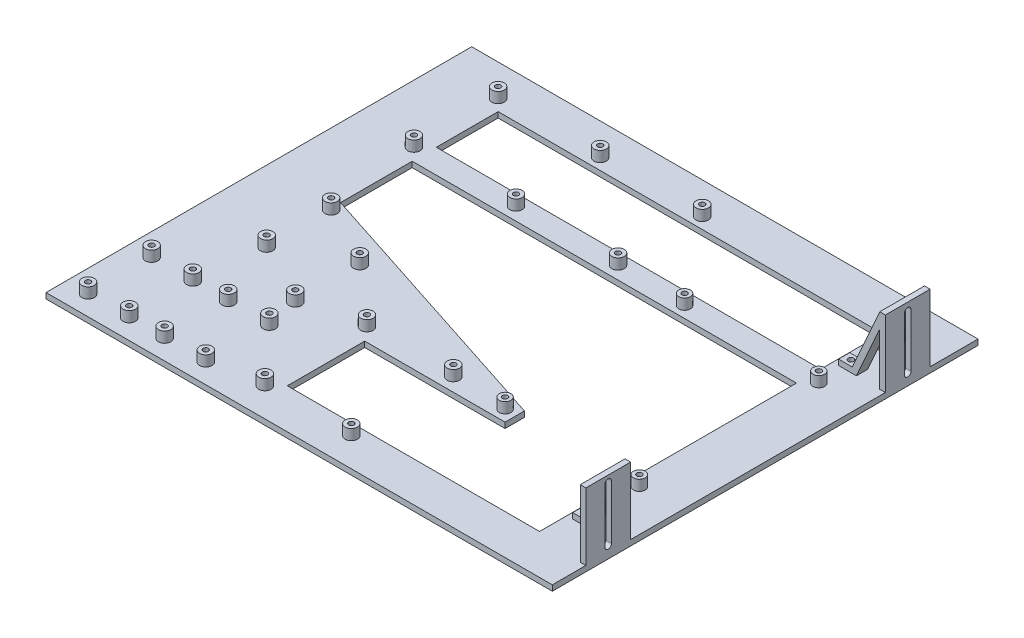
SolidWorks part; units mm, degrees
ref_plane "Front Plane" through (0, 0, 0) normal (0, 0, 1) x (1, 0, 0)
ref_plane "Top Plane" through (0, 0, 0) normal (0, 1, 0) x (1, 0, 0)
ref_plane "Right Plane" through (0, 0, 0) normal (1, 0, 0) x (0, 0, -1)
sketch "Sketch1" plane through (0, 0, 0) normal (0, 1, 0) x (1, 0, 0)
  line L1 (-143.637, -120.777) -> (143.637, -120.777)
  line L2 (-143.637, -120.777) -> (-143.637, 120.777)
  line L3 (-143.637, 120.777) -> (143.637, 120.777)
  line L4 (143.637, -120.777) -> (143.637, 120.777)
  line L5 (-143.637, -120.777) -> (143.637, 120.777) construction
  line L6 (-143.637, 120.777) -> (143.637, -120.777) construction
  point P0 (0, 0)
  dimension "D1" = 287.274
  dimension "D2" = 241.554
extrude "Boss-Extrude1" add sketch "Sketch1" along normal blind 3.175
sketch "Sketch2" plane through (0, 3.175, 0) normal (0, 1, 0) x (1, 0, 0)
  line L0 (-143.637, 93.599) -> (-143.637, 68.199)
  line L2 (-140.462, 93.599) -> (-143.637, 93.599)
  line L6 (-140.462, 68.199) -> (-140.462, 93.599)
  line L7 (-146.812, 68.199) -> (-140.462, 93.599) construction
  line L8 (-146.812, 93.599) -> (-140.462, 68.199) construction
  line L9 (-140.462, 68.199) -> (-143.637, 68.199)
  line L10 (0, 120.777) -> (0, 106.0603)
  line L11 (143.637, 120.777) -> (-143.637, 120.777) construction
  line L12 (146.812, 93.599) -> (140.462, 68.199) construction
  line L13 (146.812, 68.199) -> (140.462, 93.599) construction
  line L14 (140.462, 68.199) -> (143.637, 68.199)
  line L15 (140.462, 68.199) -> (140.462, 93.599)
  line L16 (140.462, 93.599) -> (143.637, 93.599)
  line L17 (143.637, 93.599) -> (143.637, 68.199)
  line M6 (143.637, -120.777) -> (143.637, 120.777)
  dimension "D2" = 25.4
  dimension "D3" = 6.35
extrude "Boss-Extrude3" add sketch "Sketch2" along normal blind 38.1 contours L16 L15 L14 M6
sketch "Sketch3" plane through (140.462, 0, 0) normal (-1, 0, 0) x (0, 0, 1)
  line L0 (-80.899, 36.6569) -> (-80.899, 6.3832) construction
  line L1 (-78.994, 36.6569) -> (-78.994, 6.3832)
  line L2 (-82.804, 36.6569) -> (-82.804, 6.3832)
  line L3 (-93.599, 41.275) -> (-93.599, 3.175) construction
  line L4 (-68.199, 41.275) -> (-68.199, 3.175) construction
  arc A0 (-78.994, 36.6569) -> (-82.804, 36.6569) centre (-80.899, 36.6569) ccw
  arc A1 (-82.804, 6.3832) -> (-78.994, 6.3832) centre (-80.899, 6.3832) ccw
  point P2 (-80.899, 21.5201)
  dimension "D1" = 10.795
  dimension "D2" = 10.795
extrude "Cut-Extrude1" cut sketch "Sketch3" against normal blind 25.4 contours L2 A1 L1 A0
sketch "Sketch4" plane through (0, 3.175, 0) normal (0, 1, 0) x (1, 0, 0)
  line L5 (39.497, -52.197) -> (124.587, 58.293) construction
  line L6 (39.497, 58.293) -> (124.587, -52.197) construction
  line L8 (82.042, 57.277) -> (82.042, 44.8097)
  line L9 (39.497, 3.048) -> (51.5322, 3.048)
  circle A0 centre (120.142, 53.975) radius 1.5
  circle A1 centre (120.142, 53.975) radius 3.302
  circle A2 centre (43.942, 53.975) radius 3.302
  circle A3 centre (43.942, 53.975) radius 1.5
  circle A4 centre (43.942, -47.879) radius 1.5
  circle A5 centre (43.942, -47.879) radius 3.302
  circle A6 centre (120.142, -47.879) radius 3.302
  circle A7 centre (120.142, -47.879) radius 1.5
  point P0 (82.042, 3.048)
  dimension "D7" = 3
  dimension "D1" = 76.2
  dimension "D2" = 101.854
  dimension "D3" = 110.49
  dimension "D4" = 85.09
extrude "Boss-Extrude4" add sketch "Sketch4" along normal blind 6 contours A2 A3 | A1 A0 | A5 A4 | A6 A7
sketch "Sketch5" plane through (0, 3.175, 0) normal (0, 1, 0) x (1, 0, 0)
  line L0 (143.637, 103.4969) -> (5.207, 103.4969)
  line L1 (143.637, 93.599) -> (143.637, 120.777) construction
  line L2 (5.207, 120.777) -> (5.207, 102.743)
  line L3 (143.637, 120.777) -> (-143.637, 120.777) construction
  circle A0 centre (5.207, 102.743) radius 1.5
  circle A1 centre (5.207, 102.743) radius 3.5
  circle A2 centre (5.207, 54.991) radius 1.5
  circle A3 centre (5.207, 54.991) radius 3.5
  circle A4 centre (-52.705, 54.991) radius 3.5
  circle A5 centre (-52.705, 54.991) radius 1.5
  circle A6 centre (-52.705, 102.743) radius 3.5
  circle A7 centre (-52.705, 102.743) radius 1.5
  circle A8 centre (-110.617, 54.991) radius 1.5
  circle A9 centre (-110.617, 54.991) radius 3.5
  circle A10 centre (-110.617, 102.743) radius 1.5
  circle A11 centre (-110.617, 102.743) radius 3.5
  dimension "D3" = 3
  dimension "D4" = 7
  dimension "D5" = 47.752
  dimension "D6" = 3
  dimension "D7" = 7
  dimension "D8" = 57.912
  dimension "D9" = 3
  dimension "D10" = 7
  dimension "D11" = 3
  dimension "D12" = 7
  dimension "D13" = 57.912
  dimension "D14" = 3
  dimension "D15" = 7
  dimension "D16" = 3
  dimension "D17" = 7
  dimension "D1" = 138.43
  dimension "D2" = 18.034
extrude "Boss-Extrude5" add sketch "Sketch5" along normal blind 6 contours A11 A10 | A6 A7 | L0 A1 L2 A0 | L2 A1 L0 A0 | A9 A8 | A4 A5 | A3 A2
sketch "Sketch6" plane through (0, 3.175, 0) normal (0, 1, 0) x (1, 0, 0)
  line L0 (-143.637, 120.777) -> (-143.637, -120.777) construction
  line L1 (-143.637, -120.777) -> (143.637, -120.777) construction
  circle A0 centre (-130.937, -109.601) radius 1.5
  circle A1 centre (-107.569, -109.601) radius 1.5
  circle A2 centre (-130.937, -73.533) radius 1.5
  circle A3 centre (-107.569, -73.533) radius 1.5
  circle A4 centre (-130.937, -73.533) radius 3.5
  circle A5 centre (-107.569, -73.533) radius 3.5
  circle A6 centre (-130.937, -109.601) radius 3.5
  circle A7 centre (-107.569, -109.601) radius 3.5
  circle A8 centre (-87.503, -109.601) radius 1.5
  circle A9 centre (-64.135, -109.601) radius 1.5
  circle A10 centre (-87.503, -73.533) radius 1.5
  circle A11 centre (-64.135, -73.533) radius 1.5
  circle A12 centre (-87.503, -73.533) radius 3.5
  circle A13 centre (-64.135, -73.533) radius 3.5
  circle A14 centre (-87.503, -109.601) radius 3.5
  circle A15 centre (-64.135, -109.601) radius 3.5
  dimension "D1" = 12.7
  dimension "D2" = 11.176
  dimension "D3" = 23.368
  dimension "D4" = 11.176
  dimension "D5" = 36.068
  dimension "D7" = 23.368
  dimension "D8" = 36.068
  dimension "D9" = 3
  dimension "D10" = 3
  dimension "D11" = 3
  dimension "D12" = 3
  dimension "D13" = 7
  dimension "D14" = 7
  dimension "D15" = 7
  dimension "D16" = 7
  dimension "D21" = 3
  dimension "D22" = 3
  dimension "D23" = 3
  dimension "D24" = 3
  dimension "D25" = 7
  dimension "D26" = 7
  dimension "D27" = 7
  dimension "D28" = 7
  dimension "D29" = 20.066
  dimension "D30" = 0
  dimension "D31" = 0
  dimension "D6" = 12.7
  dimension "D17" = 23.368
  dimension "D18" = 36.068
  dimension "D19" = 23.368
  dimension "D20" = 36.068
extrude "Boss-Extrude6" add sketch "Sketch6" along normal blind 6 contours A4 | A2 | A5 | A3 | A12 | A10 | A13 | A11 | A6 | A0 | A7 | A1 | A14 | A8 | A15 | A9
sketch "Sketch7" plane through (0, 3.175, 0) normal (0, 1, 0) x (1, 0, 0)
  line L0 (-143.637, 120.777) -> (-143.637, -120.777) construction
  line L1 (-143.637, -120.777) -> (143.637, -120.777) construction
  circle A0 centre (-103.251, -35.941) radius 1.5
  circle A1 centre (-68.199, -54.737) radius 1.5
  circle A2 centre (-103.251, -35.941) radius 3.5
  circle A3 centre (-68.199, -54.737) radius 3.5
  circle A4 centre (-103.251, 0.635) radius 1.5
  circle A5 centre (-68.199, -18.161) radius 1.5
  circle A6 centre (-103.251, 0.635) radius 3.5
  circle A7 centre (-68.199, -18.161) radius 3.5
  dimension "D1" = 40.386
  dimension "D2" = 84.836
  dimension "D3" = 3
  dimension "D4" = 66.04
  dimension "D5" = 75.438
  dimension "D6" = 3
  dimension "D7" = 7
  dimension "D8" = 7
  dimension "D9" = 36.576
  dimension "D10" = 0
  dimension "D11" = 36.576
  dimension "D12" = 0
  dimension "D13" = 3
  dimension "3MM" = 3
  dimension "D14" = 7
  dimension "D15" = 7
extrude "Boss-Extrude7" add sketch "Sketch7" along normal blind 6
sketch "Sketch8" plane through (0, 3.175, 0) normal (0, 1, 0) x (1, 0, 0)
  line L0 (-143.637, 120.777) -> (-143.637, -120.777) construction
  line L1 (-143.637, -120.777) -> (143.637, -120.777) construction
  circle A0 centre (-35.687, -46.609) radius 1.5
  circle A1 centre (13.335, -46.609) radius 1.5
  circle A2 centre (-35.687, -104.521) radius 1.5
  circle A3 centre (13.335, -104.521) radius 1.5
  circle A4 centre (-35.687, -46.609) radius 3.5
  circle A5 centre (13.335, -46.609) radius 3.5
  circle A6 centre (-35.687, -104.521) radius 3.5
  circle A7 centre (13.335, -104.521) radius 3.5
  dimension "D1" = 107.95
  dimension "D2" = 57.912
  dimension "D3" = 16.256
  dimension "D4" = 49.022
  dimension "D5" = 0
  dimension "D6" = 0
  dimension "D7" = 0
  dimension "D8" = 3
  dimension "D9" = 3
  dimension "D10" = 3
  dimension "D11" = 3
  dimension "D12" = 7
  dimension "D13" = 7
  dimension "D14" = 7
  dimension "D15" = 7
  dimension "D16" = 49.022
extrude "Boss-Extrude8" add sketch "Sketch8" along normal blind 6
sketch "Sketch9" plane through (0, 3.175, 0) normal (0, 1, 0) x (1, 0, 0)
  line L0 (143.637, -76.327) -> (143.637, -101.727)
  line L4 (140.462, -101.727) -> (140.462, -76.327)
  line L7 (-143.637, -120.777) -> (143.637, -120.777) construction
  line L9 (140.462, -76.327) -> (143.637, -76.327)
  line L10 (140.462, -101.727) -> (143.637, -101.727)
  dimension "D1" = 25.4
  dimension "D2" = 19.05
extrude "Boss-Extrude9" add sketch "Sketch9" along normal blind 38.1
sketch "Sketch13" plane through (140.462, 0, 0) normal (-1, 0, 0) x (0, 0, 1)
  line L0 (89.0709, 37.4464) -> (89.0709, 6.7099) construction
  line L1 (90.9759, 37.4464) -> (90.9759, 6.7099)
  line L2 (87.1659, 37.4464) -> (87.1659, 6.7099)
  arc A0 (90.9759, 37.4464) -> (87.1659, 37.4464) centre (89.0709, 37.4464) ccw
  arc A1 (87.1659, 6.7099) -> (90.9759, 6.7099) centre (89.0709, 6.7099) ccw
  point P2 (89.0709, 22.0781)
  point P7 (89.8491, 22.1559)
  point P8 (0, 0)
  point P9 (0, 0)
  point P10 (0, 0)
  point P11 (0, 0)
extrude "Cut-Extrude3" cut sketch "Sketch13" against normal blind 38.1
sketch "Sketch17" plane through (0, 0, -93.599) normal (0, 0, -1) x (-1, 0, 0)
  line L0 (-140.462, 41.275) -> (-123.444, 3.175)
  line L1 (-123.444, 3.175) -> (-127.216, 3.175)
  line L2 (-143.637, 3.175) -> (143.637, 3.175) construction
  line L3 (-127.216, 3.175) -> (-140.462, 32.8303)
  line L4 (-140.462, 41.275) -> (-140.462, 3.175) construction
  line L5 (-140.462, 32.8303) -> (-140.462, 41.275)
extrude "Boss-Extrude11" add sketch "Sketch17" against normal blind 6.35
sketch "Sketch22" plane through (0, 0, 76.327) normal (0, 0, -1) x (-1, 0, 0)
  line L0 (-140.462, 41.275) -> (-123.444, 3.175)
  line L1 (-123.444, 3.175) -> (-127.216, 3.175)
  line L2 (-127.216, 3.175) -> (-140.462, 32.8303)
  line L3 (-140.462, 32.8303) -> (-140.462, 41.275)
extrude "Boss-Extrude12" add sketch "Sketch22" against normal blind 6.35
sketch "Sketch23" plane through (0, 0, -68.199) normal (0, 0, 1) x (1, 0, 0)
  line L0 (140.462, 41.275) -> (123.444, 3.175)
  line L1 (123.444, 3.175) -> (127.216, 3.175)
  line L2 (127.216, 3.175) -> (140.462, 32.8303)
  line L3 (140.462, 32.8303) -> (140.462, 41.275)
extrude "Boss-Extrude13" add sketch "Sketch23" against normal blind 6.35
sketch "Sketch25" plane through (0, 3.175, 0) normal (0, 1, 0) x (1, 0, 0)
  line L1 (127.216, 93.599) -> (123.444, 93.599)
  line L2 (127.216, 93.599) -> (127.216, 87.249)
  line L3 (127.216, 87.249) -> (123.444, 87.249)
  line L4 (123.444, 93.599) -> (123.444, 87.249)
extrude "Boss-Extrude14" add sketch "Sketch25" along normal blind 3.175
sketch "Sketch26" plane through (123.444, 0, 0) normal (-1, 0, 0) x (0, 0, 1)
  line L1 (-93.599, 6.35) -> (-87.249, 6.35)
  line L2 (-93.599, 6.35) -> (-93.599, 3.175)
  line L3 (-93.599, 3.175) -> (-87.249, 3.175)
  line L4 (-87.249, 6.35) -> (-87.249, 3.175)
extrude "Boss-Extrude15" add sketch "Sketch26" along normal blind 6.35
sketch "Sketch27" plane through (0, 6.35, 0) normal (0, 1, 0) x (1, 0, 0)
  circle A0 centre (120.9781, 90.424) radius 1.5875
extrude "Cut-Extrude7" cut sketch "Sketch27" against normal blind 3.175
sketch "Sketch28" plane through (0, 3.175, 0) normal (0, 1, 0) x (1, 0, 0)
  line L1 (127.216, 74.549) -> (123.444, 74.549)
  line L2 (127.216, 74.549) -> (127.216, 68.199)
  line L3 (127.216, 68.199) -> (123.444, 68.199)
  line L4 (123.444, 74.549) -> (123.444, 68.199)
extrude "Boss-Extrude16" add sketch "Sketch28" along normal blind 3.175
sketch "Sketch29" plane through (123.444, 0, 0) normal (-1, 0, 0) x (0, 0, 1)
  line L1 (-74.549, 6.35) -> (-68.199, 6.35)
  line L2 (-74.549, 6.35) -> (-74.549, 3.175)
  line L3 (-74.549, 3.175) -> (-68.199, 3.175)
  line L4 (-68.199, 6.35) -> (-68.199, 3.175)
extrude "Boss-Extrude17" add sketch "Sketch29" along normal blind 6.35
sketch "Sketch30" plane through (0, 6.35, 0) normal (0, 1, 0) x (1, 0, 0)
  circle A0 centre (120.9781, 71.374) radius 1.5875
extrude "Cut-Extrude8" cut sketch "Sketch30" against normal blind 3.175
sketch "Sketch31" plane through (0, 3.175, 0) normal (0, 1, 0) x (1, 0, 0)
  line L1 (127.216, -76.327) -> (123.444, -76.327)
  line L2 (127.216, -76.327) -> (127.216, -82.677)
  line L3 (127.216, -82.677) -> (123.444, -82.677)
  line L4 (123.444, -76.327) -> (123.444, -82.677)
extrude "Boss-Extrude18" add sketch "Sketch31" along normal blind 3.175
sketch "Sketch32" plane through (123.444, 0, 0) normal (-1, 0, 0) x (0, 0, 1)
  line L0 (-120.777, 3.175) -> (120.777, 3.175) construction
  line L1 (82.677, 6.35) -> (76.327, 6.35)
  line L2 (82.677, 6.35) -> (82.677, 3.175)
  line L3 (82.677, 3.175) -> (76.327, 3.175)
  line L4 (76.327, 6.35) -> (76.327, 3.175)
  line L5 (82.677, 3.175) -> (76.327, 3.175) construction
extrude "Boss-Extrude19" add sketch "Sketch32" along normal blind 6.35
sketch "Sketch33" plane through (0, 6.35, 0) normal (0, 1, 0) x (1, 0, 0)
  circle A0 centre (120.9781, -79.502) radius 1.5875
extrude "Cut-Extrude9" cut sketch "Sketch33" against normal blind 3.175
sketch "Sketch34" plane through (0, 3.175, 0) normal (0, 1, 0) x (1, 0, 0)
  line L4 (-104.267, 96.393) -> (-104.267, 61.341)
  line L12 (113.792, 96.393) -> (113.792, 61.341)
  line L13 (-104.267, 96.393) -> (113.792, 96.393)
  line L34 (-104.267, 61.341) -> (113.792, 61.341)
  line L37 (-104.267, 47.625) -> (113.792, 47.625)
  line L38 (-104.267, 47.625) -> (-104.267, 6.985)
  line L40 (113.792, 47.625) -> (113.792, 6.985)
  line L41 (113.792, -54.229) -> (113.792, 6.985)
  line L42 (-29.337, -54.229) -> (50.292, -54.229)
  line L43 (-29.337, -54.229) -> (-29.337, -98.171)
  line L44 (-29.337, -98.171) -> (113.792, -98.171)
  line L45 (113.792, -54.229) -> (113.792, -98.171)
  line L46 (50.292, -54.229) -> (50.292, -43.2308)
  line L49 (-104.267, 6.985) -> (50.292, -43.2308)
  circle A0 centre (120.142, 53.975) radius 1.5 construction
  circle A1 centre (-110.617, 54.991) radius 1.5 construction
  circle A2 centre (43.942, 53.975) radius 1.5 construction
  circle A3 centre (13.335, -104.521) radius 1.5 construction
  circle A4 centre (43.942, -47.879) radius 1.5 construction
  circle A5 centre (-35.687, -46.609) radius 1.5 construction
  circle A6 centre (43.942, -47.879) radius 1.5 construction
  circle A9 centre (-103.251, 0.635) radius 1.5 construction
  dimension "D3" = 0
  dimension "D6" = 6.35
  dimension "D5" = 1.016
  dimension "D12" = 6.35
  dimension "D1" = 0
  dimension "D2" = 6.35
  dimension "D7" = 6.35
  dimension "D8" = 0
  dimension "D9" = 6.35
  dimension "D10" = 6.35
  dimension "D11" = 6.35
extrude "Cut-Extrude10" cut sketch "Sketch34" against normal through all
